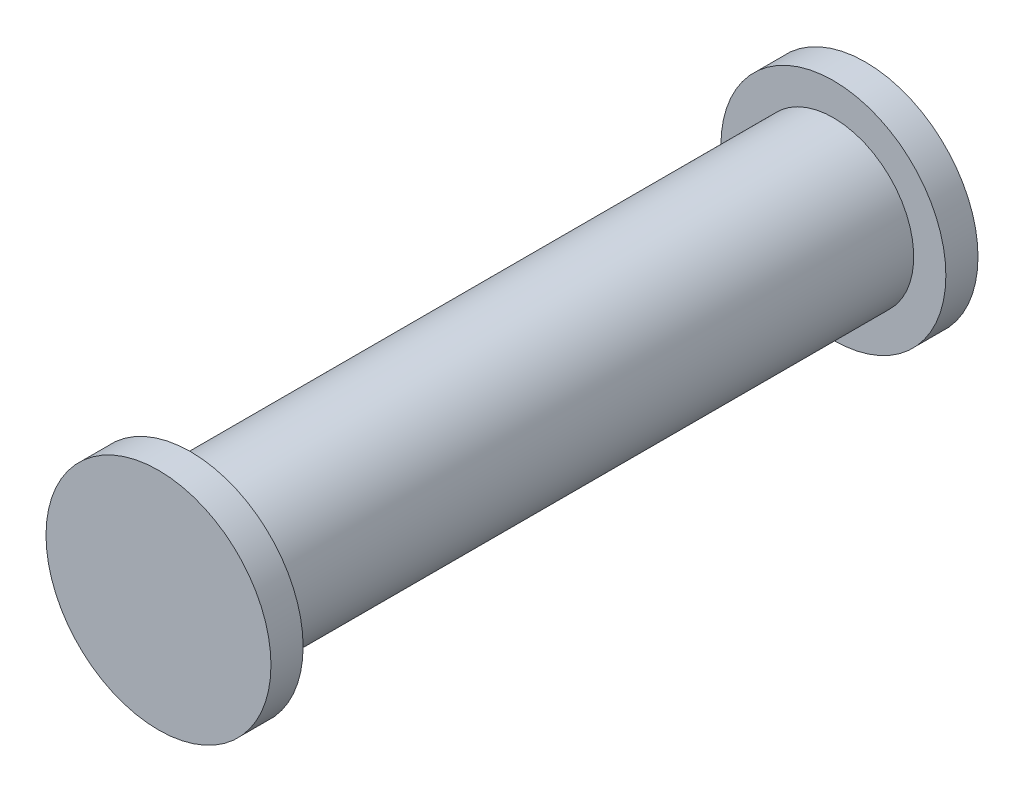
SolidWorks part; units mm, degrees
ref_plane "Front Plane" through (0, 0, 0) normal (0, 0, 1) x (1, 0, 0)
ref_plane "Top Plane" through (0, 0, 0) normal (0, 1, 0) x (1, 0, 0)
ref_plane "Right Plane" through (0, 0, 0) normal (1, 0, 0) x (0, 0, -1)
sketch "Sketch1" plane through (0, 0, 0) normal (0, 0, 1) x (1, 0, 0)
  circle A0 centre (0, 0) radius 12.5
  dimension "D1" = 25
extrude "Boss-Extrude1" add sketch "Sketch1" along normal blind 100
sketch "Sketch2" plane through (0, 0, 100) normal (0, 0, 1) x (1, 0, 0)
  circle A0 centre (0, 0) radius 17.5
  dimension "D1" = 35
extrude "Boss-Extrude2" add sketch "Sketch2" along normal blind 5
sketch "Sketch3" plane through (0, 0, 0) normal (0, 0, -1) x (-1, 0, 0)
  circle A0 centre (0, 0) radius 17.5
  dimension "D1" = 35
extrude "Boss-Extrude3" add sketch "Sketch3" along normal blind 5
